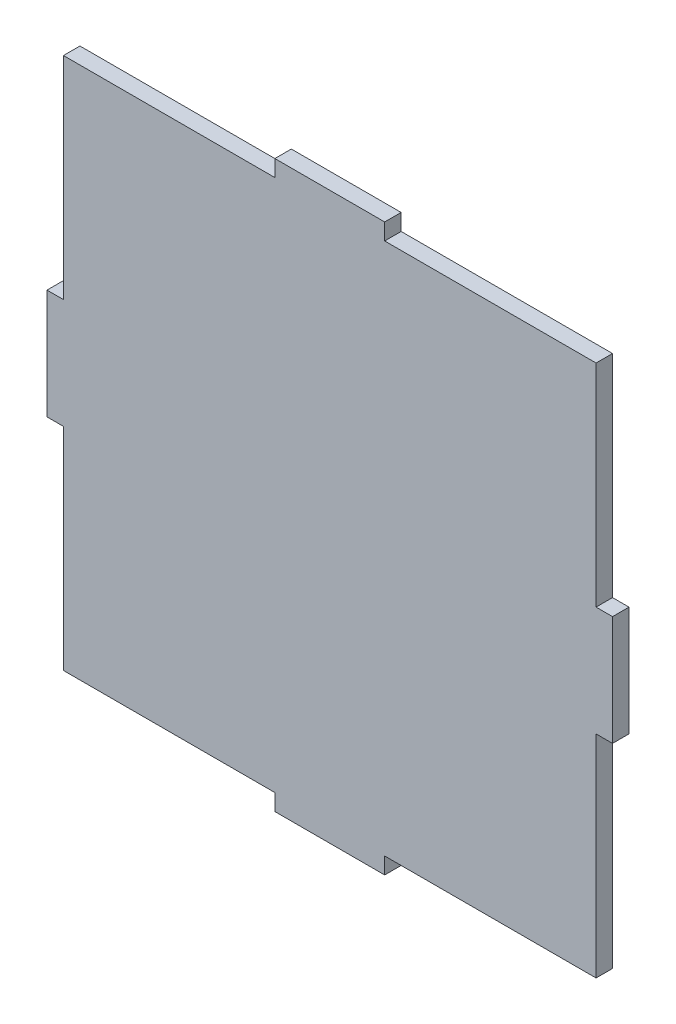
SolidWorks part; units mm, degrees
ref_plane "Front Plane" through (0, 0, 0) normal (0, 0, 1) x (1, 0, 0)
ref_plane "Top Plane" through (0, 0, 0) normal (0, 1, 0) x (1, 0, 0)
ref_plane "Right Plane" through (0, 0, 0) normal (1, 0, 0) x (0, 0, -1)
sketch "Sketch1" plane through (0, 0, 0) normal (0, 0, 1) x (1, 0, 0)
  line L4 (98.828, 101.8443) -> (98.828, 1.8443) construction
  line L5 (101.828, 1.8443) -> (1.828, 1.8443) construction
  line L6 (1.828, 98.8443) -> (1.828, -1.1557) construction
  line L7 (-1.172, 98.8443) -> (98.828, 98.8443) construction
  line L8 (98.828, 98.8443) -> (98.828, 1.8443)
  line L9 (98.828, 1.8443) -> (1.828, 1.8443)
  line L10 (1.828, 98.8443) -> (1.828, 1.8443)
  line L11 (1.828, 98.8443) -> (98.828, 98.8443)
  line L12 (60.328, 101.8443) -> (40.328, 101.8443)
  line L13 (60.328, 101.8443) -> (60.328, 98.8443)
  line L14 (40.328, 101.8443) -> (40.328, 98.8443)
  line L15 (60.328, 98.8443) -> (40.328, 98.8443)
  line L16 (60.328, 101.8443) -> (40.328, 98.8443) construction
  line L17 (40.328, 101.8443) -> (60.328, 98.8443) construction
  line L18 (1.828, 50.3443) -> (122.2922, 50.3443) construction
  line L19 (60.328, -1.1557) -> (60.328, 1.8443)
  line L20 (40.328, -1.1557) -> (40.328, 1.8443)
  line L21 (60.328, -1.1557) -> (40.328, -1.1557)
  line L22 (50.328, 98.8443) -> (50.328, 17.2668) construction
  line L23 (98.828, 60.3443) -> (101.828, 60.3443)
  line L24 (98.828, 60.3443) -> (98.828, 40.3443)
  line L25 (98.828, 40.3443) -> (101.828, 40.3443)
  line L26 (101.828, 60.3443) -> (101.828, 40.3443)
  line L27 (1.828, 40.3443) -> (-1.172, 40.3443)
  line L28 (-1.172, 60.3443) -> (-1.172, 40.3443)
  line L29 (1.828, 60.3443) -> (-1.172, 60.3443)
  point P9 (50.328, 98.8443)
  point P10 (1.828, 50.3443)
  point P12 (50.328, 100.3443)
  point P14 (50.328, 98.8443)
  point P26 (98.828, 50.3443)
  point P27 (98.828, 50.3443)
  dimension "D1" = 3
  dimension "D2" = 40.328
extrude "Boss-Extrude1" add sketch "Sketch1" along normal blind 2 and the other way blind 1 contours L12 L14 L11 L13 | L10 L29 L28 L27 | L26 L23 L8 L25 | L21 L19 L9 L20
